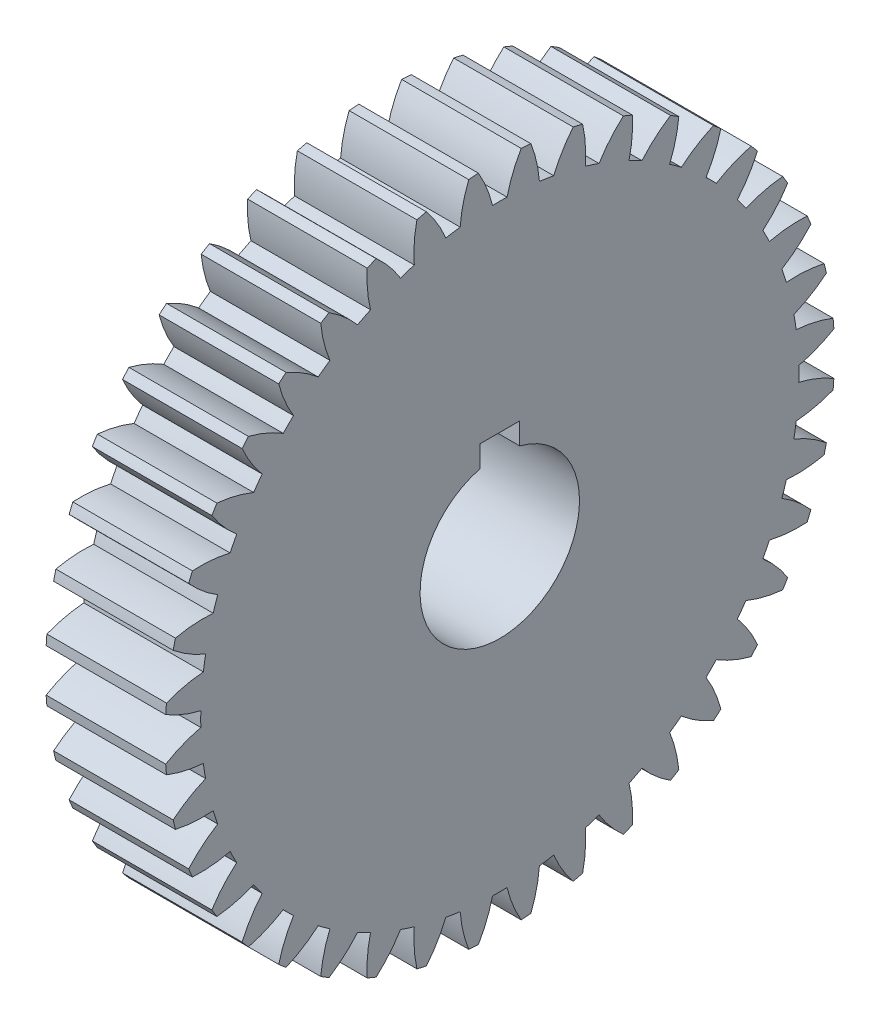
SolidWorks part; units mm, degrees
material "Plain Carbon Steel"
ref_plane "Plane1" through (0, 0, 0) normal (0, 0, 1) x (1, 0, 0)
ref_plane "Plane2" through (0, 0, 0) normal (0, 1, 0) x (1, 0, 0)
ref_plane "Plane3" through (0, 0, 0) normal (1, 0, 0) x (0, 0, -1)
sketch "HoldingSke" plane through (0, 0, 0) normal (0, 1, 0) x (1, 0, 0)
  line L0 (0, 0) -> (389.1506, -326.5361)
  line L1 (-15, 0) -> (100, 0) construction
  line L2 (0, 0) -> (-2.1039, 2.3779)
  line L3 (0, 0) -> (-11.863, 4.5341)
  line L4 (0, 0) -> (6.6156, 5.5511)
  line L5 (0, 0) -> (-20.8238, -7.7667)
  line L6 (0, 0) -> (-7.8959, -5.3274)
  line L7 (-2.1039, 2.3779) -> (2.68, 24.082)
  line L8 (-76.2, 54.61) -> (-61.976, 54.61)
  line L9 (-71.009, 38.7566) -> (-53.1078, 45.2721)
  line L10 (-76.2, 71.12) -> (104.1128, 71.12)
  line L11 (0, 0) -> (-9.525, 0)
  line L12 (-76.2, 101.6) -> (-76.1492, 101.6)
  line L13 (24.9733, 27.94) -> (52.9518, 28.4284)
  line L14 (24.9733, 27.94) -> (25.0241, 27.9398)
  line L15 (24.9733, 27.94) -> (100.4021, 29.52)
  circle A0 centre (0, 0) radius 6.35
  circle A1 centre (0, 0) radius 23.0124
  circle A2 centre (0, 0) radius 23.0124
  circle A3 centre (0, 0) radius 6.35
  dimension "MHD" = 46.0248
  dimension "Hub_dia" = 46.0248
  dimension "Bore" = 12.7
  dimension "MBD" = 12.7
  dimension "Num_teeth" = 40
  dimension "Pitch_radius" = 180.3128
  dimension "Pitch" = 508
  dimension "Width" = 9.525
  dimension "Overall_len" = 22.225
  dimension "Show_teeth" = 40
  dimension "Thickness" = 9.525
  dimension "OAL" = 22.2251
  dimension "T_dim" = 14.224
  dimension "Ap" = 20
  dimension "H" = 19.05
  dimension "Backlash" = 0.0508
  dimension "Addendum_fac" = 1
  dimension "Dedendum_fac" = 1.2
  dimension "Clearance_fac" = 0.2
  dimension "Dedendum_add" = 0.0508
sketch "BasProSke" plane through (0, 0, 0) normal (0, 1, 0) x (1, 0, 0)
  line L0 (-10, 0) -> (60, 0) construction
  line L1 (0, 0) -> (0, 26.67)
  line L2 (0, 0) -> (9.525, 0)
  line L3 (9.525, 0) -> (9.525, 26.67)
  line L4 (9.525, 26.67) -> (0, 26.67)
  dimension "Diameter" = 53.34
  dimension "Thickness" = 9.525
revolve "Base-Revolve" add sketch "BasProSke" angle 360 about L0
sketch "TooCutSke" plane through (0, 0, 0) normal (1, 0, 0) x (0, 0, -1)
  line L1 (0, 0) -> (0, 107) construction
  line L2 (0, 0) -> (-1.0861, 25.3768) construction
  line L3 (0, 0) -> (-3.9832, 50.611) construction
  line L4 (-1.0861, 25.3768) -> (-1.9916, 25.3055) construction
  arc A0 (0.5773, 23.8182) -> (-0.5773, 23.8182) centre (0, 0) ccw
  arc A1 (1.7213, 26.6399) -> (-1.7213, 26.6399) centre (0, 0) ccw
  circle A2 centre (0, 0) radius 25.4 construction
  circle A3 centre (0, 0) radius 23.8682 construction
  arc A4 (-0.5773, 23.8182) -> (-1.7213, 26.6399) centre (-10.4586, 21.4548) ccw
  arc A5 (1.7213, 26.6399) -> (0.5773, 23.8182) centre (10.4586, 21.4548) ccw
  dimension "Root_dia" = 47.6504
  dimension "Overcut_dia" = 53.3908
  dimension "Pitch_dia" = 50.8
  dimension "Base_dia" = 47.7364
  dimension "Flank_rad" = 10.16
  dimension "Half_ang" = 4.5
  dimension "Half_CT" = 0.9083
extrude "ToothCut" cut sketch "TooCutSke" along normal through all
fillet "Breaks" [suppressed] radius 0.0254
fillet "RootFillets" [suppressed] radius 0.3048
pattern_circular "TeethCuts" count 40 every 9 about axis through (-10, 0, 0) along (1, 0, 0) of "ToothCut", "RootFillets", "Breaks"
sketch "HubNeaOneSke" plane through (0, 0, 0) normal (-1, 0, 0) x (0, 0, 1)
  circle A0 centre (0, 0) radius 23.0124
  dimension "Diameter" = 46.0248
extrude "HubNearOne" add sketch "HubNeaOneSke" along normal blind 12.7001
sketch "HubNeaBotSke" plane through (0, 0, 0) normal (-1, 0, 0) x (0, 0, 1)
  circle A0 centre (0, 0) radius 23.0124
  dimension "Diameter" = 46.0248
extrude "HubNearBoth" [suppressed] add sketch "HubNeaBotSke" along normal blind 6.35
ref_plane "FarPln" through (9.525, 0, 0) normal (1, 0, 0) x (0, 0, -1)
sketch "HubFarSke" plane through (9.525, 0, 0) normal (1, 0, 0) x (0, 0, -1)
  circle A0 centre (0, 0) radius 23.0124
  dimension "Diameter" = 46.0248
extrude "HubFar" [suppressed] add sketch "HubFarSke" along normal blind 6.35
sketch "BorSke" plane through (0, 0, 0) normal (1, 0, 0) x (0, 0, -1)
  circle A0 centre (0, 0) radius 6.35
  dimension "Diameter" = 12.7
extrude "Bore" cut sketch "BorSke" along normal mid plane 44.4501
sketch "KeySke" plane through (0, 0, 0) normal (1, 0, 0) x (0, 0, -1)
  line L0 (-1.5875, 0) -> (-1.5875, 7.874)
  line L1 (-1.5875, 7.874) -> (1.5875, 7.874)
  line L2 (1.5875, 7.874) -> (1.5875, 0)
  line L3 (0, 0) -> (0, 34) construction
  line L4 (-1.5875, 0) -> (1.5875, 0)
  dimension "Offset" = 7.874
  dimension "Width" = 3.175
extrude "Keyway" cut sketch "KeySke" along normal mid plane 44.4501
pattern_circular "Keyway2" [suppressed] count 2 every 90 about axis through (-10, 0, 0) along (1, 0, 0)
sketch "Sketch1" plane through (-12.7001, 0, 0) normal (-1, 0, 0) x (0, 0, 1)
  circle A0 centre (0, 0) radius 11.1125
  circle A1 centre (0, 0) radius 23.0124
  circle A2 centre (0, 0) radius 23.0124 construction
  dimension "D1" = 22.225
extrude "Cut-Extrude1" cut sketch "Sketch1" against normal up to surface (12.7001 mm away) up to face at (0, 0, 0)
sketch "Sketch2" plane through (-12.7001, 0, 0) normal (-1, 0, 0) x (0, 0, 1)
  circle A0 centre (0, 0) radius 11.1125
  circle A1 centre (0, 0) radius 11.1125 construction
extrude "Cut-Extrude2" cut sketch "Sketch2" against normal blind 5.08
equation "' \"Pitch@HoldingSke\" = 4"
equation "' \"Num_teeth@HoldingSke\" = 12"
equation "' \"Ap@HoldingSke\" =  20"
equation "' \"Width@HoldingSke\" = 0.5"
equation "' \"Hub_dia@HoldingSke\"= 1"
equation "' \"Overall_len@HoldingSke\" = 1.0"
equation "' \"Bore@HoldingSke\" = 0.75"
equation "' \"T_dim@HoldingSke\" = 0.85"
equation "' \"Width@KeySke\" = 0.25"
equation "' \"Show_teeth@HoldingSke\" = 13"
equation "' \"Backlash@HoldingSke\" = 0.009"
equation "' \"Addendum_fac@HoldingSke\" = 1.0"
equation "' \"Dedendum_fac@HoldingSke\" = 1.25"
equation "' \"Dedendum_add@HoldingSke\" = 0.00005"
equation "' \"Clearance_fac@HoldingSke\" = 0.25"
equation "' \"Pitch@HoldingSke\" = 0.5"
equation "' \"Num_teeth@HoldingSke\" = 23"
equation "' \"Show_teeth@HoldingSke\" = 23"
equation "' \"Backlash@HoldingSke\" = 0.0375"
equation "\"Overcut_dia@TooCutSke\" = (\"Num_teeth@HoldingSke\" + 2 * \"Addendum_fac@HoldingSke\") / \"Pitch@HoldingSke\" + 0.002"
equation "\"Pitch_dia@TooCutSke\" = \"Num_teeth@HoldingSke\" / \"Pitch@HoldingSke\""
equation "\"Base_dia@TooCutSke\" = \"Num_teeth@HoldingSke\" / \"Pitch@HoldingSke\" * cos((\"Ap@HoldingSke\"  * 3.14159265 / 180))"
equation "\"Root_dia@TooCutSke\" = (\"Num_teeth@HoldingSke\" + 2) / \"Pitch@HoldingSke\" - 2 * (\"Addendum_fac@HoldingSke\" + \"Dedendum_fac@HoldingSke\") / \"Pitch@HoldingSke\" - \"Dedendum_add@HoldingSke\" * 2"
equation "\"Half_ang@TooCutSke\" = 180 / \"Num_teeth@HoldingSke\""
equation "\"Half_CT@TooCutSke\" = \"Num_teeth@HoldingSke\" / \"Pitch@HoldingSke\" * sin((3.14159265 / 2 / \"Num_teeth@HoldingSke\")) / 2 - 7 * \"Backlash@HoldingSke\" / 4"
equation "\"Flank_rad@TooCutSke\" = \"Num_teeth@HoldingSke\" / \"Pitch@HoldingSke\" / 5"
equation "\"Radius@RootFillets\" = \"Clearance_fac@HoldingSke\" / \"Pitch@HoldingSke\" + \"Dedendum_add@HoldingSke\""
equation "\"Break_rad@Breaks\" = 0.02 / \"Pitch@HoldingSke\""
equation "\"Thickness@HoldingSke\" = \"Width@HoldingSke\""
equation "\"OAL@HoldingSke\" = \"Thickness@HoldingSke\""
equation "\"MHD@HoldingSke\" = (\"Num_teeth@HoldingSke\" + 2) / \"Pitch@HoldingSke\" - 2 * (\"Addendum_fac@HoldingSke\" + \"Dedendum_fac@HoldingSke\")  / \"Pitch@HoldingSke\" - \"Dedendum_add@HoldingSke\" * 2"
equation "\"MBD@HoldingSke\" = (\"Num_teeth@HoldingSke\" + 2) / \"Pitch@HoldingSke\" - 2 * (\"Addendum_fac@HoldingSke\" + \"Dedendum_fac@HoldingSke\")  / \"Pitch@HoldingSke\" - \"Dedendum_add@HoldingSke\" * 2 - 0.002"
equation "\"MHD@HoldingSke\" = ((sgn( \"MHD@HoldingSke\" - \"Hub_dia@HoldingSke\" )-1)*( \"MHD@HoldingSke\" - \"Hub_dia@HoldingSke\" ))/-2+ \"Hub_dia@HoldingSke\""
equation "\"MBD@HoldingSke\" = ((sgn( \"MBD@HoldingSke\" - \"Bore@HoldingSke\" )-1)*( \"MBD@HoldingSke\" - \"Bore@HoldingSke\" ))/-2+ \"Bore@HoldingSke\""
equation "\"OAL@HoldingSke\" = ((sgn( \"OAL@HoldingSke\" - \"Overall_len@HoldingSke\" )+1)*( \"OAL@HoldingSke\" - \"Overall_len@HoldingSke\" ))/2 + \"Overall_len@HoldingSke\" + 0.000002"
equation "\"Num_teeth@TeethCuts\" = int( \"Show_teeth@HoldingSke\" ) + 1"
equation "\"Num_teeth@TeethCuts\" = ((sgn( \"Num_teeth@TeethCuts\" - \"Num_teeth@HoldingSke\" )-1)*( \"Num_teeth@TeethCuts\" - \"Num_teeth@HoldingSke\" ))/-2+ \"Num_teeth@HoldingSke\""
equation "\"Num_teeth@TeethCuts\" = ((sgn( \"Num_teeth@TeethCuts\" - 2.0)+1)*( \"Num_teeth@TeethCuts\" - 2.0))/2 +2.0"
equation "\"Angle@TeethCuts\" = 360.0 / \"Num_teeth@HoldingSke\""
equation "\"Diameter@BasProSke\" = (\"Num_teeth@HoldingSke\" + 2 * \"Addendum_fac@HoldingSke\") / \"Pitch@HoldingSke\""
equation "\"Thickness@BasProSke\"  = \"Thickness@HoldingSke\""
equation "' \"Fillet_rad@BasProSke\" =  \"Thickness@HoldingSke\" * 0.05"
equation "\"MHD@HoldingSke\" = ((sgn( \"MHD@HoldingSke\" - \"Root_dia@TooCutSke\" )-1)*( \"MHD@HoldingSke\" - \"Root_dia@TooCutSke\" ))/-2+ \"Root_dia@TooCutSke\""
equation "\"Diameter@HubNeaOneSke\" = \"MHD@HoldingSke\""
equation "\"Length@HubNearOne\" = \"OAL@HoldingSke\" - \"Thickness@BasProSke\""
equation "\"Diameter@HubNeaBotSke\" = \"MHD@HoldingSke\""
equation "\"Length@HubNearBoth\" = ( \"OAL@HoldingSke\" - \"Thickness@BasProSke\" ) / 2.0"
equation "\"Thickness@FarPln\" = \"Thickness@BasProSke\""
equation "\"Diameter@HubFarSke\" = \"MHD@HoldingSke\""
equation "\"Length@HubFar\" = ( \"OAL@HoldingSke\" - \"Thickness@BasProSke\" ) / 2.0"
equation "\"Diameter@BorSke\" = \"MBD@HoldingSke\""
equation "\"D1@Bore\" = \"OAL@HoldingSke\" * 2.0"
equation "\"D1@Keyway\" = \"OAL@HoldingSke\" * 2.0"
equation "\"Offset@KeySke\" = \"T_dim@HoldingSke\" - \"MBD@HoldingSke\" / 2.0"
